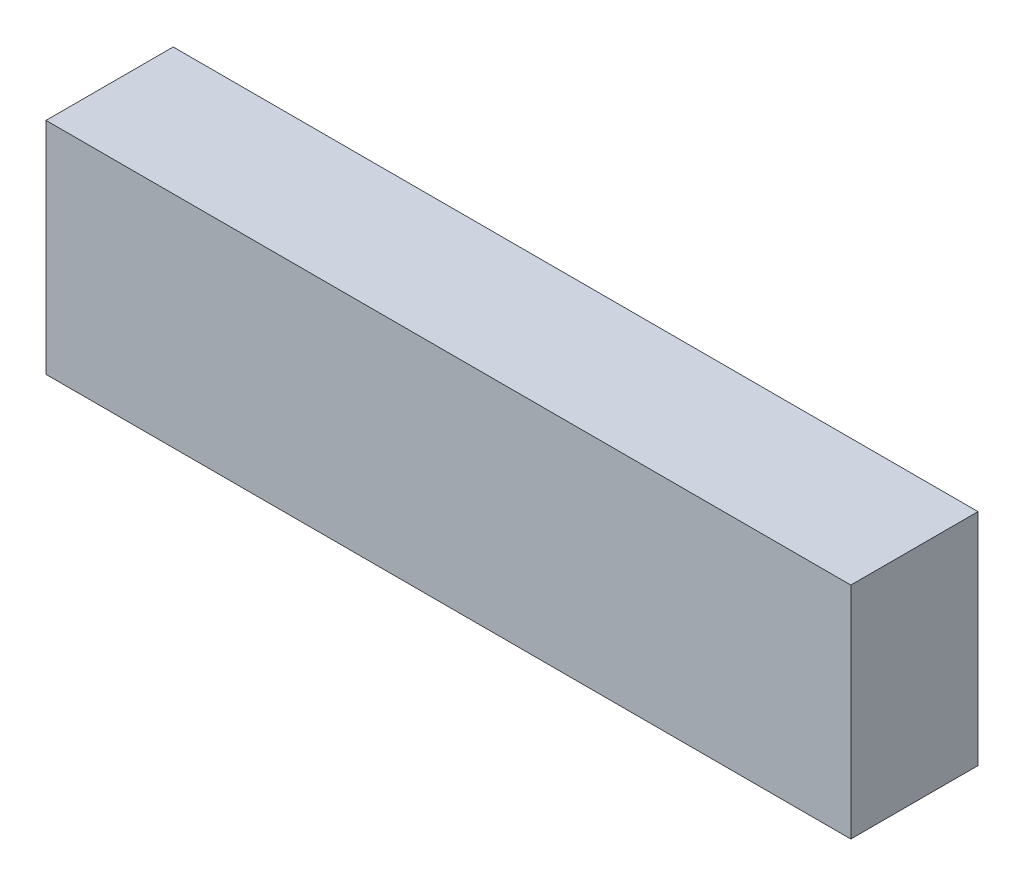
SolidWorks part; units mm, degrees
ref_plane "Front Plane" through (0, 0, 0) normal (0, 0, 1) x (1, 0, 0)
ref_plane "Top Plane" through (0, 0, 0) normal (0, 1, 0) x (1, 0, 0)
ref_plane "Right Plane" through (0, 0, 0) normal (1, 0, 0) x (0, 0, -1)
sketch "Sketch1" plane through (0, 0, 0) normal (0, 0, 1) x (1, 0, 0)
  line L0 (7.6645, 30.39) -> (53.9445, 30.39) construction
  line L1 (7.8645, 30.19) -> (53.7445, 30.19)
  line L2 (7.8645, 30.19) -> (7.8645, 17.65)
  line L3 (7.8645, 17.65) -> (53.7445, 17.65)
  line L4 (53.7445, 30.19) -> (53.7445, 17.65)
  line L5 (53.9445, 30.39) -> (53.9445, 17.45) construction
  line L6 (53.9445, 17.45) -> (7.6645, 17.45) construction
  line L7 (7.6645, 17.45) -> (7.6645, 30.39) construction
  dimension "D1" = 0.2
  dimension "D2" = 0.2
  dimension "D3" = 0.2
  dimension "D4" = 0.2
extrude "Boss-Extrude1" add sketch "Sketch1" along normal blind 7.25 contours L1 L4 L3 L2
shell "Shell1" thickness 0.5
equation "\"D2@Sketch1\"=\"D1@Sketch1\""
equation "\"D3@Sketch1\"=\"D1@Sketch1\""
equation "\"D4@Sketch1\"=\"D1@Sketch1\""
